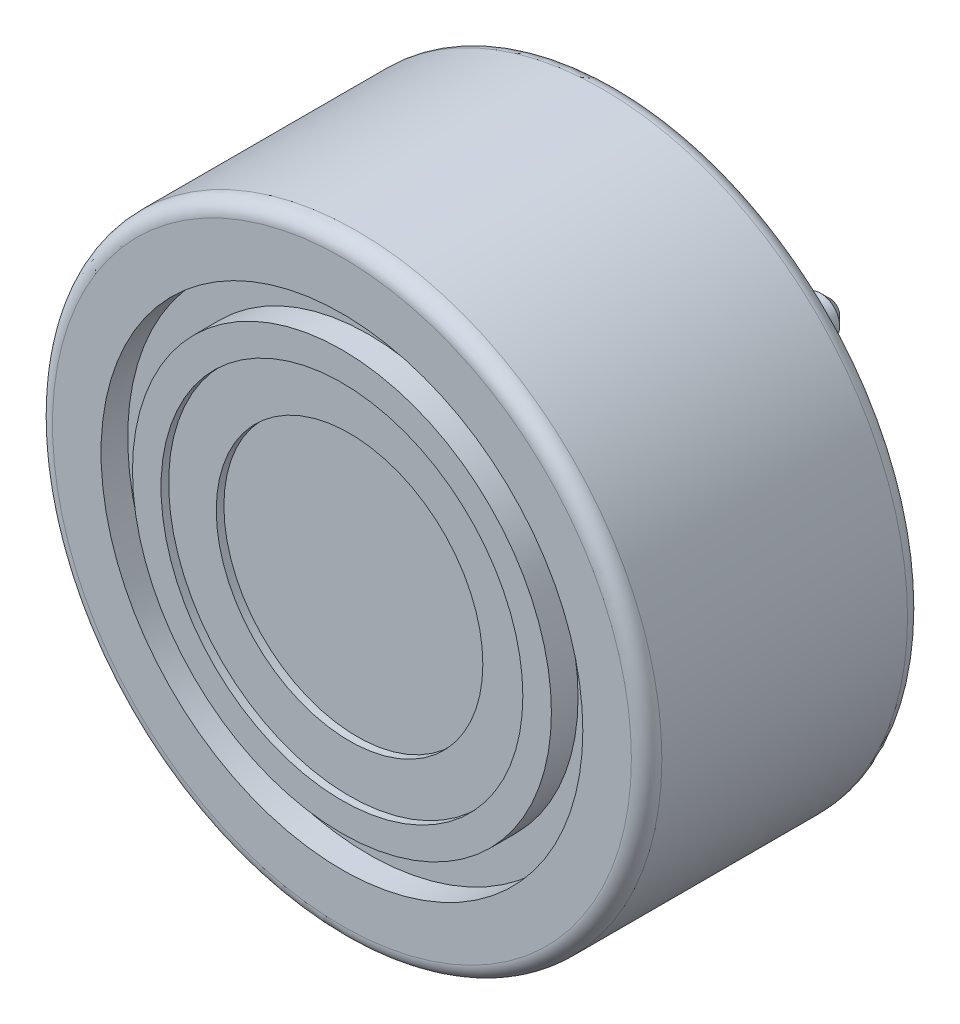
SolidWorks part; units mm, degrees
ref_plane "Спереди" through (0, 0, 0) normal (0, 0, 1) x (1, 0, 0)
ref_plane "Сверху" through (0, 0, 0) normal (0, 1, 0) x (1, 0, 0)
ref_plane "Справа" through (0, 0, 0) normal (1, 0, 0) x (0, 0, -1)
sketch "Эскиз1" plane through (0, 0, 0) normal (0, 0, 1) x (1, 0, 0)
  circle A0 centre (0, 0) radius 16
  dimension "D1" = 32
extrude "Бобышка-Вытянуть1" add sketch "Эскиз1" along normal blind 14.5
sketch "Эскиз2" plane through (0, 0, 0) normal (0, 0, -1) x (-1, 0, 0)
  circle A0 centre (0, 0) radius 12
  circle A1 centre (0, 0) radius 10.9
  dimension "D1" = 24
  dimension "D2" = 21.8
extrude "Бобышка-Вытянуть2" add sketch "Эскиз2" along normal blind 1.4
sketch "Эскиз3" plane through (0, 0, 0) normal (0, 0, -1) x (-1, 0, 0)
  circle A0 centre (0, 0) radius 10.9
extrude "Бобышка-Вытянуть3" add sketch "Эскиз3" along normal blind 1
sketch "Эскиз4" plane through (0, 0, 14.5) normal (0, 0, 1) x (1, 0, 0)
  circle A0 centre (0, 0) radius 12.65
  circle A1 centre (0, 0) radius 11
  dimension "D1" = 25.3
  dimension "D2" = 22
extrude "Вырез-Вытянуть1" cut sketch "Эскиз4" against normal blind 1.4
sketch "Эскиз5" plane through (0, 0, 14.5) normal (0, 0, 1) x (1, 0, 0)
  circle A0 centre (0, 0) radius 9.5
  dimension "D1" = 19
extrude "Вырез-Вытянуть2" cut sketch "Эскиз5" against normal blind 0.4
sketch "Эскиз6" plane through (0, 0, 14.1) normal (0, 0, 1) x (1, 0, 0)
  circle A0 centre (0, 0) radius 7
  dimension "D1" = 14
extrude "Вырез-Вытянуть3" cut sketch "Эскиз6" against normal blind 0.4
sketch "Эскиз7" plane through (0, 0, -1) normal (0, 0, -1) x (-1, 0, 0)
  circle A0 centre (0, 0) radius 8.4 construction
  circle A1 centre (-8.4, 0) radius 1
  circle A2 centre (8.4, 0) radius 1
  circle A3 centre (-5.939, -5.9404) radius 1
  circle A4 centre (-5.939, 5.9404) radius 1
  point P11 (0, 0)
  point P12 (0, 0)
  dimension "D1" = 16.8
  dimension "D2" = 2
  dimension "D4" = 6.43
  dimension "D3" = 6.43
extrude "Бобышка-Вытянуть4" add sketch "Эскиз7" along normal blind 4.2
chamfer "Фаска1" distance 0.5 angle 45 4 edges at (4.939, 5.9404, -5.2) (-9.4, 0, -5.2) (7.4, 0, -5.2) (4.939, -5.9404, -5.2)
fillet "Скругление1" radius 0.8 2 edges at (16, 0, 0) (16, 0, 14.5)
fillet "Скругление2" radius 0.2 2 edges at (-10.9, 0, -1.4) (-12, 0, -1.4)
